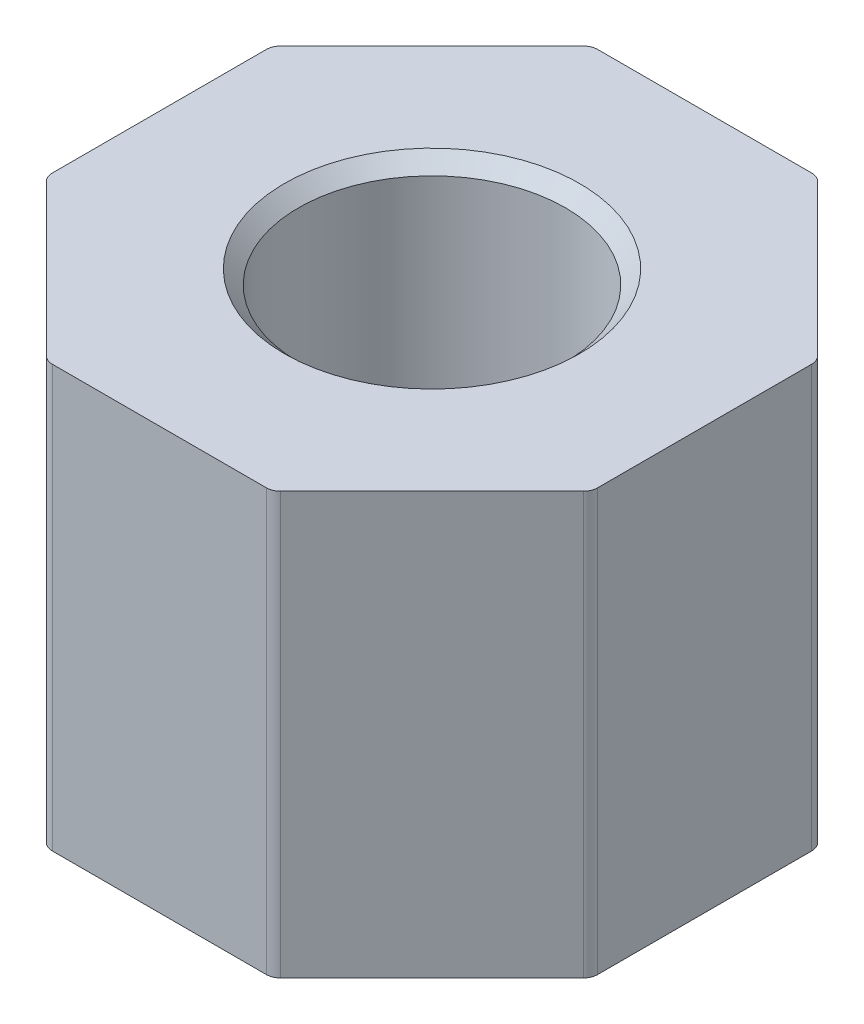
SolidWorks part; units mm, degrees
ref_plane "Front Plane" through (0, 0, 0) normal (0, 0, 1) x (1, 0, 0)
ref_plane "Top Plane" through (0, 0, 0) normal (0, 1, 0) x (1, 0, 0)
ref_plane "Right Plane" through (0, 0, 0) normal (1, 0, 0) x (0, 0, -1)
sketch "Sketch2" plane through (0, 0, 0) normal (0, 1, 0) x (1, 0, 0)
  line L0 (19.4015, -8.0364) -> (19.4015, 8.0364)
  line L1 (8.0364, 19.4015) -> (-8.0364, 19.4015)
  line L2 (-8.0364, 19.4015) -> (-19.4015, 8.0364)
  line L3 (-19.4015, 8.0364) -> (-19.4015, -8.0364)
  line L4 (-19.4015, -8.0364) -> (-8.0364, -19.4015)
  line L5 (-8.0364, -19.4015) -> (8.0364, -19.4015)
  line L6 (8.0364, -19.4015) -> (19.4015, -8.0364)
  line L7 (19.4015, 8.0364) -> (8.0364, 19.4015)
  circle A0 centre (0, 0) radius 21 construction
  dimension "D1" = 42
extrude "Boss-Extrude1" add sketch "Sketch2" along normal blind 30
sketch "Sketch3" plane through (0, 30, 0) normal (0, 1, 0) x (1, 0, 0)
  circle A0 centre (0, 0) radius 9.5
  dimension "D1" = 19
extrude "Cut-Extrude1" cut sketch "Sketch3" against normal through all
chamfer "Chamfer1" distance 1 angle 45 2 edges at (0, 0, 9.5) (0, 30, 9.5)
fillet "Fillet1" radius 1 8 edges at (-19.4015, 15, 8.0364) (-8.0364, 15, 19.4015) (8.0364, 15, 19.4015) (19.4015, 15, 8.0364) (19.4015, 15, -8.0364) (8.0364, 15, -19.4015) (-8.0364, 15, -19.4015) (-19.4015, 15, -8.0364)
